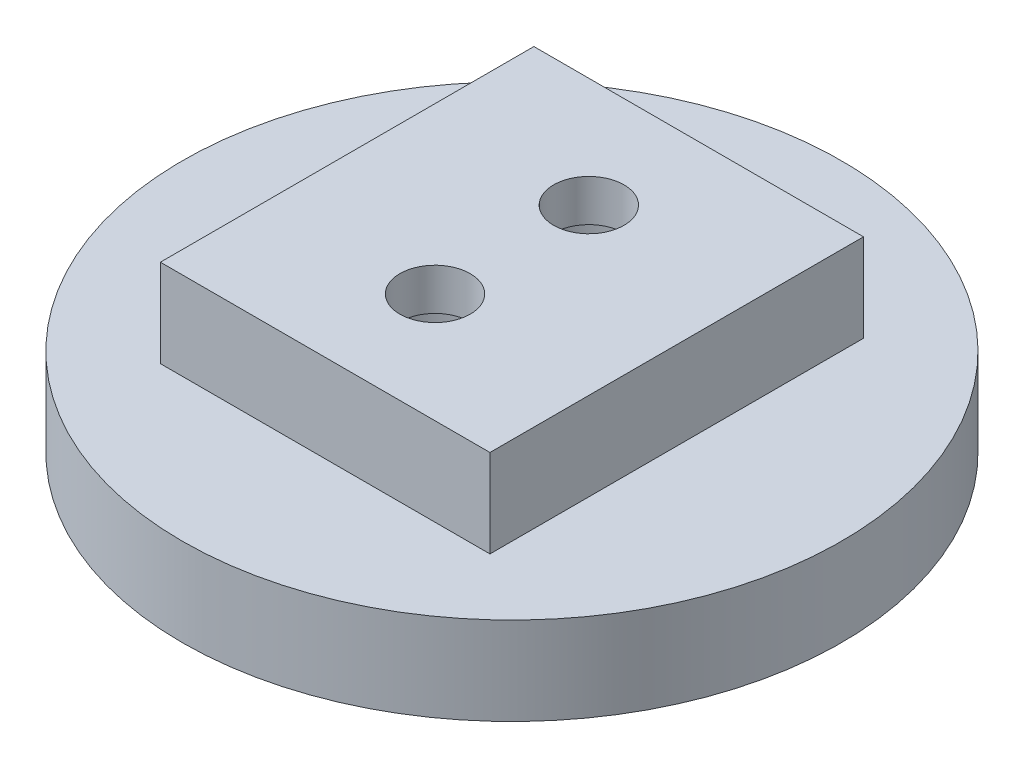
SolidWorks part; units mm, degrees
ref_plane "Front Plane" through (0, 0, 0) normal (0, 0, 1) x (1, 0, 0)
ref_plane "Top Plane" through (0, 0, 0) normal (0, 1, 0) x (1, 0, 0)
ref_plane "Right Plane" through (0, 0, 0) normal (1, 0, 0) x (0, 0, -1)
sketch "Sketch2" plane through (0, 0, 0) normal (0, 1, 0) x (1, 0, 0)
  circle A0 centre (0, 0) radius 15
  dimension "D1" = 30
extrude "Boss-Extrude1" add sketch "Sketch2" along normal blind 4
sketch "Sketch3" plane through (0, 4, 0) normal (0, 1, 0) x (1, 0, 0)
  line L1 (-7.5, -8.5) -> (7.5, -8.5)
  line L2 (-7.5, -8.5) -> (-7.5, 8.5)
  line L3 (-7.5, 8.5) -> (7.5, 8.5)
  line L4 (7.5, -8.5) -> (7.5, 8.5)
  line L5 (-7.5, -8.5) -> (7.5, 8.5) construction
  line L6 (-7.5, 8.5) -> (7.5, -8.5) construction
  point P0 (0, 0)
  dimension "D1" = 15
  dimension "D2" = 17
extrude "Boss-Extrude2" add sketch "Sketch3" along normal blind 4
sketch "Sketch4" plane through (0, 8, 0) normal (0, 1, 0) x (1, 0, 0)
  line L0 (7.5, 0) -> (-7, 0) construction
  line L1 (0, 8.5) -> (0, -17.71) construction
  line L2 (-4.3265, 3.5) -> (4.3265, 3.5) construction
  line L3 (-4.3265, -3.5) -> (4.3265, -3.5) construction
  line L4 (7.5, -8.5) -> (7.5, 8.5)
  line L16 (7.5, -8.5) -> (7.5, 8.5)
  line L20 (7.5, 8.5) -> (-7.5, 8.5)
  line L22 (7.5, 8.5) -> (-7.5, 8.5)
  line L24 (-7.5, 8.5) -> (-7.5, -8.5)
  line L25 (-7.5, 8.5) -> (-7.5, -8.5)
  line L26 (-7.5, -8.5) -> (7.5, -8.5)
  line L27 (-7.5, -8.5) -> (7.5, -8.5)
  circle A0 centre (0, 3.5) radius 1.6
  circle A1 centre (0, -3.5) radius 1.6
  point P0 (0, 0)
  point P1 (7.5, 0)
  point P14 (0, 3.5)
  dimension "D2" = 3.2
  dimension "D3" = 7
  dimension "D1" = 0
extrude "Cut-Extrude1" cut sketch "Sketch4" against normal through all contours A0 | A1
sketch "Sketch5" plane through (0, 0, 0) normal (0, -1, 0) x (1, 0, 0)
  line L0 (-15, 0) -> (15, 0) construction
  line L1 (0, 15) -> (0, -15) construction
  line L2 (-1.6, 3.5) -> (1.6, 3.5) construction
  line L3 (-1.6, -3.5) -> (1.6, -3.5) construction
  circle A0 centre (0, 3.5) radius 1.6 construction
  circle A1 centre (0, 0) radius 15
  circle A2 centre (0, 0) radius 15
  circle A3 centre (0, -3.5) radius 1.6 construction
  circle A4 centre (0, 3.5) radius 2.95
  circle A5 centre (0, -3.5) radius 2.95
  point P17 (0, 3.5)
  point P18 (0, -3.5)
  dimension "D2" = 5.9
  dimension "D1" = 0
extrude "Cut-Extrude2" cut sketch "Sketch5" against normal blind 6.1 contours A5 | A4
